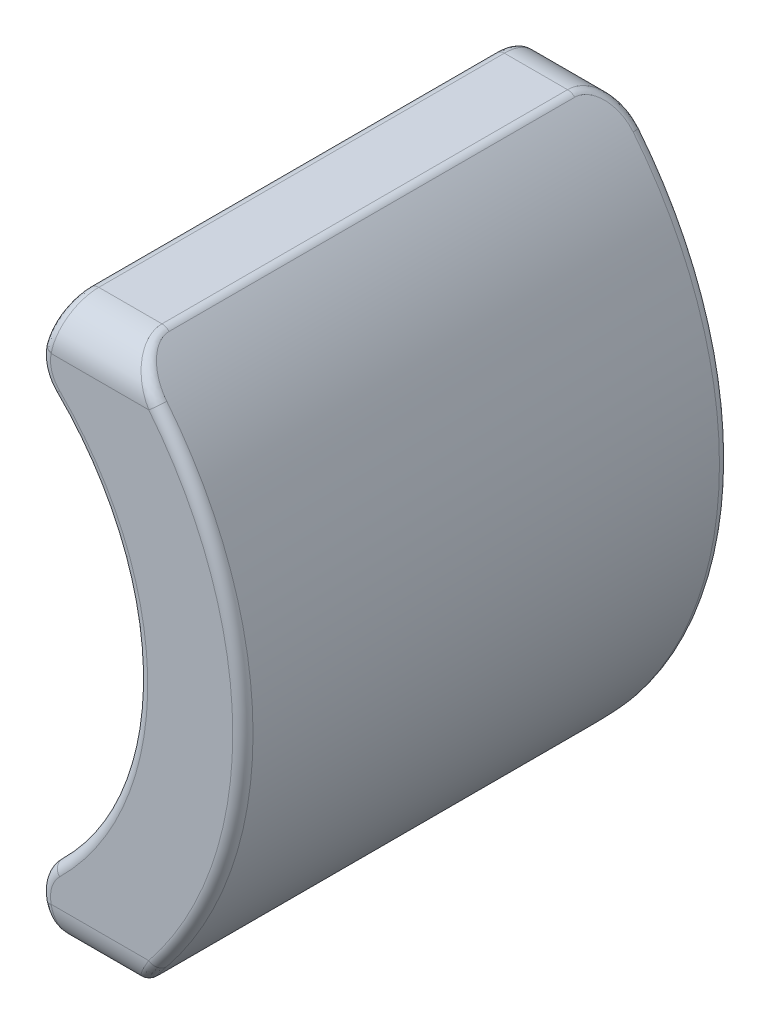
SolidWorks part; units mm, degrees
ref_plane "Front Plane" through (0, 0, 0) normal (0, 0, 1) x (1, 0, 0)
ref_plane "Top Plane" through (0, 0, 0) normal (0, 1, 0) x (1, 0, 0)
ref_plane "Right Plane" through (0, 0, 0) normal (1, 0, 0) x (0, 0, -1)
sketch "Sketch1" plane through (0, 0, 0) normal (0, 0, 1) x (1, 0, 0)
  line L0 (0, 0) -> (9.63, 0) construction
  line L1 (6.7381, -6.88) -> (4.8781, -6.88)
  line L2 (4.8781, -6.88) -> (4.5318, -5.38)
  line L3 (4.8781, 6.88) -> (4.5318, 5.38)
  line L4 (6.7381, 6.88) -> (4.8781, 6.88)
  arc A0 (6.7381, 6.88) -> (6.7381, -6.88) centre (0, 0) cw
  arc A1 (4.5318, 5.38) -> (4.5318, -5.38) centre (0, 0) cw
  point P7 (9.63, 0)
  dimension "D1" = 9.63
  dimension "D2" = 6.88
  dimension "D3" = 103
  dimension "D4" = 1.86
  dimension "D5" = 1.5
extrude "Boss-Extrude1" add sketch "Sketch1" along normal blind 12
fillet "Fillet1" radius 1 2 edges at (4.5318, -5.38, 6) (4.5318, 5.38, 6)
fillet "Fillet2" radius 1 4 edges at (5.8081, -6.88, 12) (5.8081, -6.88, 0) (5.8081, 6.88, 0) (5.8081, 6.88, 12)
fillet "Fillet3" radius 0.25 24 edges at (6.9882, -6.6258, 11.6661) (6.7381, -6.88, 6) (6.8685, -6.7498, 0.5066) (9.63, 0, 0) (6.9882, 6.6258, 0.3339) (6.7381, 6.88, 6) (6.8685, 6.7498, 11.4934) (4.8161, 6.6112, 11.6822) (4.8781, 6.88, 6) (4.8161, 6.6112, 0.3178) (4.6879, 5.4113, 0) (7.0343, 0, 0) (4.6879, -5.4113, 0) (4.8161, -6.6112, 0.3178) (4.8781, -6.88, 6) (4.8161, -6.6112, 11.6822) (7.0343, 0, 12) (4.6879, 5.4113, 12) (9.63, 0, 12) (4.6879, -5.4113, 12)
